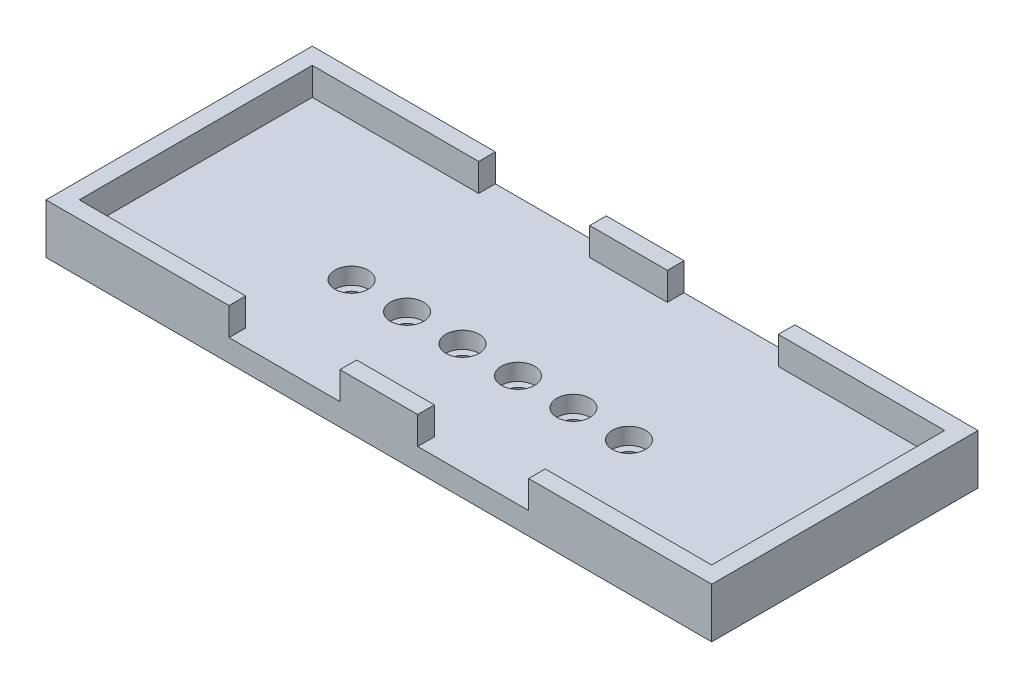
SolidWorks part; units mm, degrees
ref_plane "Front Plane" through (0, 0, 0) normal (0, 0, 1) x (1, 0, 0)
ref_plane "Top Plane" through (0, 0, 0) normal (0, 1, 0) x (1, 0, 0)
ref_plane "Right Plane" through (0, 0, 0) normal (1, 0, 0) x (0, 0, -1)
sketch "Sketch1" plane through (0, 0, 0) normal (0, 1, 0) x (1, 0, 0)
  line L1 (-50.2611, 20.0764) -> (69.7389, 20.0764)
  line L2 (-50.2611, 20.0764) -> (-50.2611, -27.9236)
  line L3 (-50.2611, -27.9236) -> (69.7389, -27.9236)
  line L4 (69.7389, 20.0764) -> (69.7389, -27.9236)
  dimension "D1" = 120
  dimension "D2" = 48
extrude "Boss-Extrude1" add sketch "Sketch1" along normal blind 4 contours L2 L3 L4 L1
sketch "Sketch2" plane through (0, 4, 0) normal (0, 1, 0) x (1, 0, 0)
  line L0 (-50.2611, -27.9236) -> (69.7389, -27.9236) construction
  line L1 (-50.2611, 20.0764) -> (-17.2611, 20.0764)
  line L2 (-50.2611, 20.0764) -> (-50.2611, -27.9236)
  line L3 (-50.2611, -27.9236) -> (-17.2611, -27.9236)
  line L4 (69.7389, 20.0764) -> (69.7389, -27.9236)
  line L5 (-17.2611, 20.0764) -> (-17.2611, 17.0764)
  line L6 (-47.2611, 17.0764) -> (-17.2611, 17.0764)
  line L7 (-47.2611, 17.0764) -> (-47.2611, -24.9236)
  line L8 (-47.2611, -24.9236) -> (-17.2611, -24.9236)
  line L9 (66.7389, 17.0764) -> (66.7389, -24.9236)
  line L10 (-17.2611, -24.9236) -> (-17.2611, -27.9236)
  line L11 (36.7389, 20.0764) -> (36.7389, 17.0764)
  line L12 (2.7389, 20.0764) -> (2.7389, 17.0764)
  line L13 (16.7389, 20.0764) -> (16.7389, 17.0764)
  line L14 (2.7389, 20.0764) -> (16.7389, 20.0764)
  line L15 (2.7389, 17.0764) -> (16.7389, 17.0764)
  line L16 (2.7389, -24.9236) -> (16.7389, -24.9236)
  line L17 (2.7389, -27.9236) -> (16.7389, -27.9236)
  line L18 (36.7389, -27.9236) -> (69.7389, -27.9236)
  line L19 (36.7389, -24.9236) -> (66.7389, -24.9236)
  line L20 (36.7389, 20.0764) -> (69.7389, 20.0764)
  line L21 (36.7389, 17.0764) -> (66.7389, 17.0764)
  line L22 (36.7389, -24.9236) -> (36.7389, -27.9236)
  line L23 (16.7389, -24.9236) -> (16.7389, -27.9236)
  line L24 (2.7389, -24.9236) -> (2.7389, -27.9236)
  line L25 (69.7389, 20.0764) -> (69.7389, -27.9236) construction
  dimension "D1" = 3
  dimension "D2" = 3
  dimension "D3" = 3
  dimension "D4" = 3
  dimension "D5" = 30
  dimension "D6" = 30
  dimension "D7" = 20
  dimension "D8" = 20
  dimension "D9" = 0
extrude "Boss-Extrude2" add sketch "Sketch2" along normal blind 5
sketch "Sketch3" plane through (0, 4, 0) normal (0, 1, 0) x (1, 0, 0)
  line L0 (-47.2611, -2.8485) -> (66.7389, -2.8485) construction
  line L1 (-47.2611, -24.9236) -> (-47.2611, 17.0764) construction
  line L2 (66.7389, 17.0764) -> (66.7389, -24.9236) construction
  line L5 (16.7389, -24.9236) -> (2.7389, -24.9236) construction
  line L6 (-16.0086, -2.8485) -> (-16.0086, -7.8485)
  line L11 (9.7389, -2.8485) -> (24.9889, -7.8485) construction
  line L12 (-5.5111, -7.8485) -> (9.7389, -2.8485) construction
  line L13 (-16.0086, -7.8485) -> (36.369, -7.8485) construction
  line L14 (9.7389, -2.8485) -> (9.7389, -24.9236) construction
  circle A0 centre (4.7389, -7.8485) radius 1.7
  circle A1 centre (-5.2611, -7.8485) radius 1.7
  circle A2 centre (-15.2611, -7.8485) radius 1.7
  circle A3 centre (34.7389, -7.8485) radius 1.7
  circle A4 centre (24.7389, -7.8485) radius 1.7
  circle A5 centre (14.7389, -7.8485) radius 1.7
  point P12 (9.7389, -2.8485)
  dimension "D1" = 3.4
  dimension "D2" = 5
  dimension "D3" = 5
  dimension "D4" = 3
extrude "Cut-Extrude1" cut sketch "Sketch3" against normal blind 5 contours A0 | A1 | A2 | A5 | A4 | A3
sketch "Sketch4" plane through (0, 4, 0) normal (0, 1, 0) x (1, 0, 0)
  circle A32 centre (-15.2611, -7.8485) radius 3
  circle A33 centre (-5.2611, -7.8485) radius 3
  circle A34 centre (4.7389, -7.8485) radius 3
  circle A35 centre (14.7389, -7.8485) radius 3
  circle A36 centre (24.7389, -7.8485) radius 3
  circle A37 centre (34.7389, -7.8485) radius 3
  dimension "D1" = 6
extrude "Cut-Extrude2" cut sketch "Sketch4" against normal blind 3
